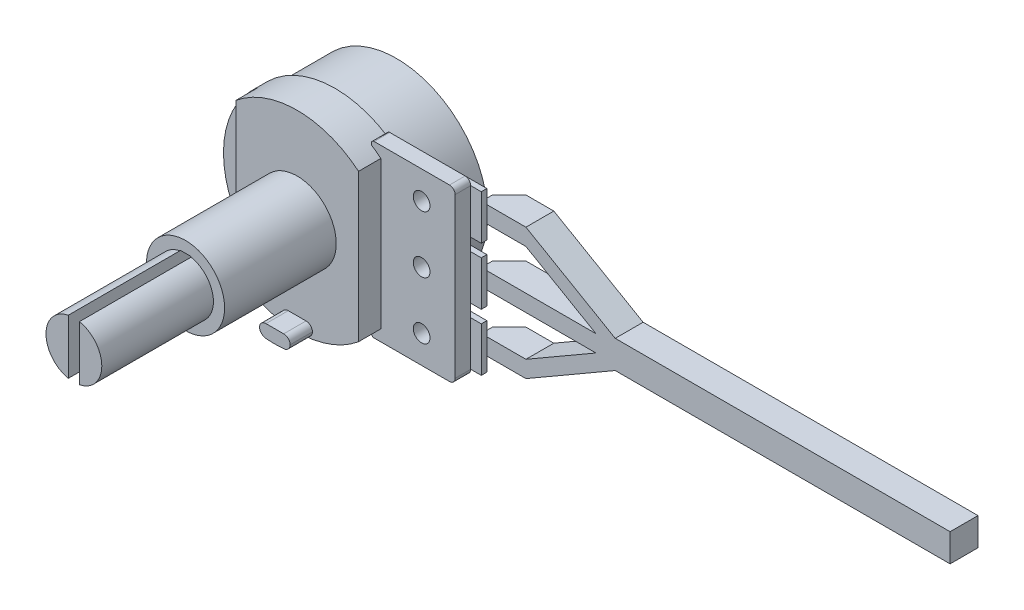
SolidWorks part; units mm, degrees
ref_plane "Спереди" through (0, 0, 0) normal (0, 0, 1) x (1, 0, 0)
ref_plane "Сверху" through (0, 0, 0) normal (0, 1, 0) x (1, 0, 0)
ref_plane "Справа" through (0, 0, 0) normal (1, 0, 0) x (0, 0, -1)
sketch "Эскиз2" plane through (0, 0, 0) normal (0, 0, 1) x (1, 0, 0)
  circle A0 centre (0, 0) radius 8.175
extrude "Бобышка-Вытянуть1" add sketch "Эскиз2" along normal blind 5.5
sketch "Эскиз3" plane through (0, 0, 5.5) normal (0, 0, 1) x (1, 0, 0)
  line L0 (4.65, -7.375) -> (4.65, -7.2345)
  line L1 (4.9, 7.625) -> (11.65, 7.625)
  line L3 (4.9, -7.625) -> (11.65, -7.625)
  line L4 (12.15, 7.125) -> (12.15, -7.125)
  line L5 (0, -50) -> (0, 50) construction
  line L8 (4.65, 7.375) -> (4.65, 7.2345)
  arc A0 (4.65, 7.2345) -> (4.65, -7.2345) centre (0, 0) ccw
  arc A1 (11.65, -7.625) -> (12.15, -7.125) centre (11.65, -7.125) ccw
  arc A2 (12.15, 7.125) -> (11.65, 7.625) centre (11.65, 7.125) ccw
  arc A3 (4.65, -7.375) -> (4.9, -7.625) centre (4.9, -7.375) ccw
  arc A5 (4.65, 7.375) -> (4.9, 7.625) centre (4.9, 7.375) cw
  point P22 (12.15, 0)
  dimension "D2" = 0.5
  dimension "D3" = 7.5
  dimension "D5" = 0.25
  dimension "D6" = 0.25
  dimension "D1" = 15.25
  dimension "D4" = 12.15
extrude "Бобышка-Вытянуть2" add sketch "Эскиз3" along normal blind 1.4
sketch "Эскиз5" plane through (0, 0, 0) normal (0, 0, -1) x (-1, 0, 0)
  line L1 (-1.25, -5.675) -> (1.25, -5.675)
  line L2 (-1.25, -5.675) -> (-1.25, -8.175)
  line L3 (-1.25, -8.175) -> (1.25, -8.175)
  line L4 (1.25, -5.675) -> (1.25, -8.175)
  line L6 (0, 50) -> (0, -50) construction
  circle A1 centre (0, 0) radius 8.175 construction
  point P5 (0, -8.175)
  dimension "D1" = 2.5
  dimension "D2" = 2.5
extrude "Вырез-Вытянуть1" cut sketch "Эскиз5" against normal blind 2.5
sketch "Эскиз6" plane through (0, 0, 6.9) normal (0, 0, 1) x (1, 0, 0)
  line L0 (-5.5, 6.6114) -> (-5.5, -6.6114)
  line L1 (5.5, 6.6114) -> (5.5, -6.6114)
  line L2 (0, -50) -> (0, 50) construction
  arc A0 (5.5, 6.6114) -> (-5.5, 6.6114) centre (0, 0) ccw
  arc A1 (-5.5, -6.6114) -> (5.5, -6.6114) centre (0, 0) ccw
  dimension "D1" = 5.5
  dimension "D3" = 8.6
  dimension "D2" = 5.5
extrude "Бобышка-Вытянуть3" add sketch "Эскиз6" along normal blind 2
sketch "Эскиз7" plane through (0, 0, 8.9) normal (0, 0, 1) x (1, 0, 0)
  circle A0 centre (0, 0) radius 3.5
extrude "Бобышка-Вытянуть4" add sketch "Эскиз7" along normal blind 10
sketch "Эскиз8" plane through (0, 0, 18.9) normal (0, 0, 1) x (1, 0, 0)
  circle A0 centre (0, 0) radius 2.5
extrude "Бобышка-Вытянуть5" add sketch "Эскиз8" along normal blind 10
sketch "Эскиз9" plane through (0, 0, 28.9) normal (0, 0, 1) x (1, 0, 0)
  line L1 (-0.5, 2.5) -> (0.5, 2.5)
  line L2 (-0.5, 2.5) -> (-0.5, -2.5)
  line L3 (-0.5, -2.5) -> (0.5, -2.5)
  line L4 (0.5, 2.5) -> (0.5, -2.5)
  line L5 (0, -50) -> (0, 50) construction
  circle A0 centre (0, 0) radius 2.5 construction
  circle A1 centre (0, 0) radius 2.5 construction
  point P4 (0, 2.5)
  point P9 (0, -2.5)
  dimension "D1" = 1
extrude "Вырез-Вытянуть5" cut sketch "Эскиз9" against normal blind 11.5
sketch "Эскиз12" plane through (0, 0, 5.5) normal (0, 0, -1) x (-1, 0, 0)
  line L0 (-9.15, -2) -> (-13.0958, -2)
  line L1 (-9.15, 7.1259) -> (-13.0958, 7.1259)
  line L3 (-9.15, 3.1259) -> (-13.0958, 3.1259)
  line L4 (-13.0958, 7.1259) -> (-13.0958, 3.1259)
  line L5 (-9.15, 2) -> (-13.0958, 2)
  line L6 (-13.0958, 2) -> (-13.0958, -2)
  line L7 (-13.0958, -3.125) -> (-13.0958, -7.125)
  line L8 (-9.15, -7.125) -> (-13.0958, -7.125)
  line L9 (-9.15, -3.125) -> (-13.0958, -3.125)
  arc A0 (-9.15, -2) -> (-8.0084, -1.6422) centre (-9.15, 0) ccw
  arc A1 (-9.15, -7.125) -> (-9.15, -3.125) centre (-9.15, -5.125) ccw
  arc A2 (-8.0084, 1.6422) -> (-8.0084, -1.6422) centre (0, 0) ccw
  arc A3 (-9.15, 3.1259) -> (-9.15, 7.1259) centre (-9.15, 5.1259) ccw
  arc A4 (-8.0084, 1.6422) -> (-9.15, 2) centre (-9.15, 0) ccw
  point P6 (-9.15, 5.1259)
  point P7 (-9.15, 0)
  point P14 (-9.15, -5.125)
  dimension "D1" = 4
  dimension "D2" = 4
  dimension "D3" = 4
extrude "Бобышка-Вытянуть6" add sketch "Эскиз12" along normal blind 0.5
sketch "Эскиз14" plane through (0, 0, 5) normal (0, 0, -1) x (-1, 0, 0)
  line L0 (-16.5958, 5.8759) -> (-26.7578, 0)
  line L1 (-16.5958, 5.8759) -> (-12.5958, 5.8759)
  line L2 (-16.5958, 5.8759) -> (-16.5958, 4.3759)
  line L3 (-16.5958, 4.3759) -> (-12.5958, 4.3759)
  line L4 (-12.5958, 5.8759) -> (-12.5958, 4.3759)
  line L5 (-12.5958, 0.75) -> (-12.5958, -0.75)
  line L6 (-16.5958, 0.75) -> (-16.5958, -0.75)
  line L7 (-16.5958, 0.75) -> (-12.5958, 0.75)
  line L8 (-16.5958, -0.75) -> (-12.5958, -0.75)
  line L9 (-16.5958, -5.875) -> (-12.5958, -5.875)
  line L10 (-16.5958, -4.375) -> (-12.5958, -4.375)
  line L11 (-16.5958, -4.375) -> (-16.5958, -5.875)
  line L12 (-12.5958, -4.375) -> (-12.5958, -5.875)
  line L13 (50, 0) -> (-50, 0) construction
  line L14 (-26.7578, 0) -> (-16.5958, 0)
  line L15 (-26.7578, 0) -> (-16.5958, -5.875)
  line L16 (-24.5958, 1.2501) -> (-54.5958, 1.2501)
  line L17 (-24.5958, -1.2499) -> (-54.5958, -1.2499)
  line L18 (-54.5958, 1.2501) -> (-54.5958, -1.2499)
  line L19 (-16.5958, 0.75) -> (-22.8665, 0.75)
  line L20 (-16.5958, -0.75) -> (-22.8663, -0.75)
  line L21 (-16.5958, 4.3759) -> (-24.1636, 0)
  line L22 (-16.5958, -4.375) -> (-24.1636, 0)
  line M13 (-13.0958, 7.1259) -> (-13.0958, 3.1259)
  dimension "D1" = 1.5
  dimension "D2" = 4
  dimension "D3" = 4.375
  dimension "D4" = 30
  dimension "D5" = 8
  dimension "D6" = 2.5
  dimension "D7" = 12.5958
  dimension "D8" = 4.3759
extrude "Бобышка-Вытянуть7" add sketch "Эскиз14" along normal blind 2.5 separate body contours L2 L3 L1 M13 | L4 L1 L3 M13 | L6 L8 L5 L7 | L12 L10 L11 L9 | L21 L2 L0 L14 | L22 L20 L6 L14 | L19 L21 L14 L6 | L11 L22 L14 L15 | L16 L18 L17 L15 L0
sketch "Эскиз11" plane through (0, 0, 6.9) normal (0, 0, 1) x (1, 0, 0)
  line L3 (11.65, 7.625) -> (4.9, 7.625) construction
  line L6 (12.15, -7.125) -> (12.15, 7.125) construction
  circle A0 centre (9.15, 5.125) radius 0.75
  circle A1 centre (9.15, 0) radius 0.75
  circle A2 centre (9.15, -5.125) radius 0.75
  dimension "D1" = 3
  dimension "D2" = 2.5
  dimension "D4" = 3
  dimension "D5" = 3
extrude "Вырез-Вытянуть6" cut sketch "Эскиз11" against normal up to next
chamfer "Фаска1" distance 1.5 3 edges at (12.5958, -5.125, 2.5) (12.5958, 0, 2.5) (12.5958, 5.1259, 2.5)
sketch "Эскиз пенька" plane through (0, 0, 8.9) normal (0, 0, 1) x (1, 0, 0)
  line L0 (-0.795, -7.35) -> (0.795, -7.35)
  line L4 (0, -50) -> (0, 50) construction
  line L5 (-1.375, -7.93) -> (-1.375, -7.8843)
  line L6 (1.375, -7.93) -> (1.375, -7.8843)
  arc A1 (-0.8141, -8.5015) -> (0.8141, -8.5015) centre (0, 0) ccw
  arc A3 (-1.375, -7.8843) -> (-0.8141, -8.5015) centre (-0.755, -7.8843) ccw
  arc A4 (1.375, -7.8843) -> (0.8141, -8.5015) centre (0.755, -7.8843) cw
  arc A5 (1.375, -7.93) -> (0.795, -7.35) centre (0.795, -7.93) ccw
  arc A6 (-1.375, -7.93) -> (-0.795, -7.35) centre (-0.795, -7.93) cw
  point P11 (0, -7.35)
  point P15 (1.375, -7.35)
  point P18 (-1.375, -7.35)
  dimension "D1" = 7.35
  dimension "D3" = 0.62
  dimension "D4" = 0.62
  dimension "D5" = 0.58
  dimension "D2" = 2.75
extrude "Бобышка-пенек резистора" add sketch "Эскиз пенька" along normal blind 2 contours A6 A3 A1 A4 A5 L0
